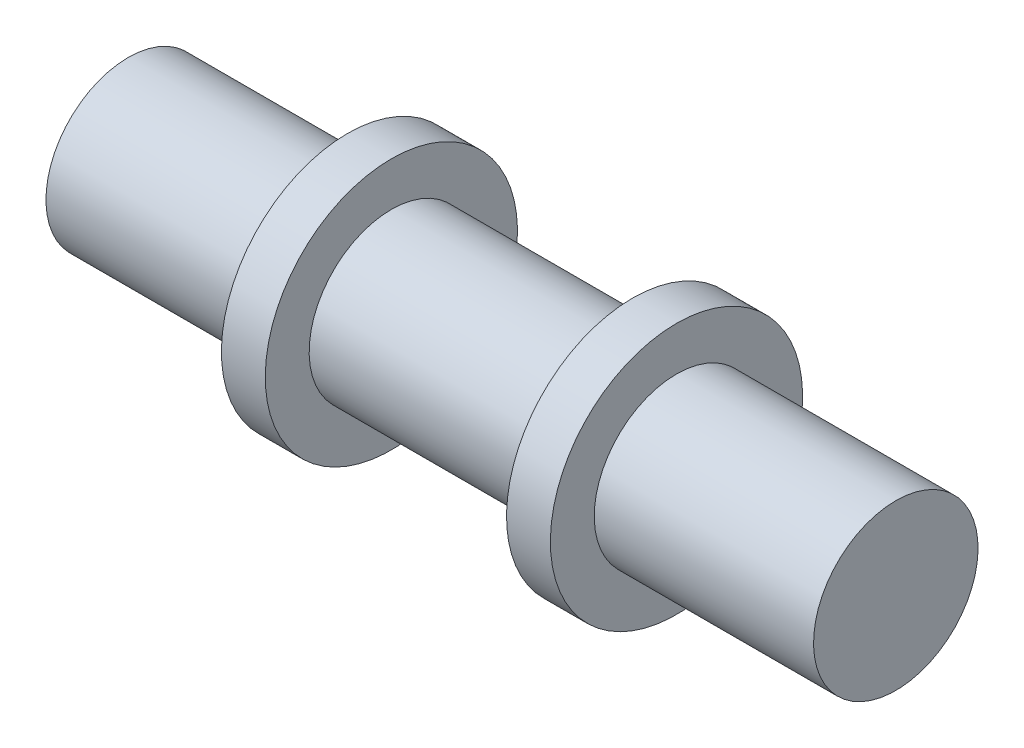
SolidWorks part; units mm, degrees
ref_plane "Front Plane" through (0, 0, 0) normal (0, 0, 1) x (1, 0, 0)
ref_plane "Top Plane" through (0, 0, 0) normal (0, 1, 0) x (1, 0, 0)
ref_plane "Right Plane" through (0, 0, 0) normal (1, 0, 0) x (0, 0, -1)
sketch "Sketch2" plane through (0, 0, 0) normal (0, 0, 1) x (1, 0, 0)
  line L0 (88.9, 0) -> (-88.9, 0)
  line L1 (-88.9, 0) -> (-88.9, 19.05)
  line L2 (-88.9, 19.05) -> (-38.1, 19.05)
  line L3 (-38.1, 19.05) -> (-38.1, 29.21)
  line L4 (-38.1, 29.21) -> (-27.94, 29.21)
  line L5 (-27.94, 29.21) -> (-27.94, 19.05)
  line L6 (-27.94, 19.05) -> (27.94, 19.05)
  line L8 (27.94, 29.21) -> (27.94, 19.05)
  line L9 (38.1, 29.21) -> (27.94, 29.21)
  line L10 (38.1, 19.05) -> (38.1, 29.21)
  line L11 (88.9, 19.05) -> (38.1, 19.05)
  line L12 (88.9, 0) -> (88.9, 19.05)
  dimension "D2" = 19.05
  dimension "D3" = 10.16
  dimension "D5" = 10.16
  dimension "D6" = 50.8
revolve "Revolve1" add sketch "Sketch2" angle 360 about L0
